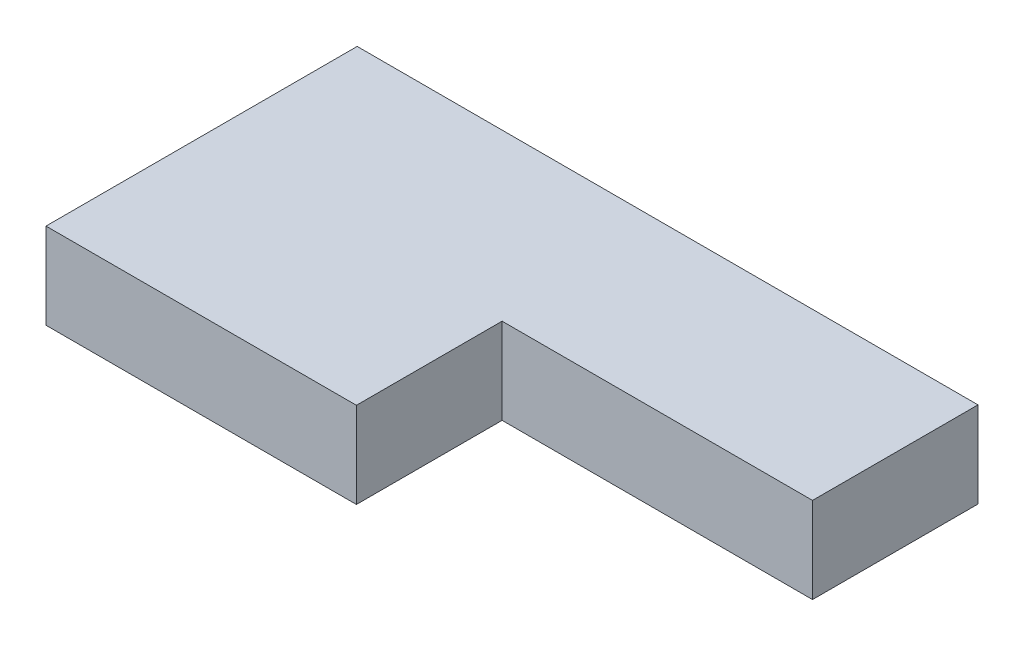
SolidWorks part; units mm, degrees
ref_plane "Front Plane" through (0, 0, 0) normal (0, 0, 1) x (1, 0, 0)
ref_plane "Top Plane" through (0, 0, 0) normal (0, 1, 0) x (1, 0, 0)
ref_plane "Right Plane" through (0, 0, 0) normal (1, 0, 0) x (0, 0, -1)
sketch "Sketch1" plane through (0, 0, 0) normal (0, 1, 0) x (1, 0, 0)
  line L0 (0, 40.6807) -> (91.7709, 40.6807)
  line L1 (91.7709, 40.6807) -> (91.7709, 16.2191)
  line L2 (91.7709, 16.2191) -> (45.8855, 16.2191)
  line L3 (45.8855, 16.2191) -> (45.8855, -5.3177)
  line L4 (45.8855, -5.3177) -> (0, -5.3177)
  line L5 (0, -5.3177) -> (0, 40.6807)
extrude "Extrude1" add sketch "Sketch1" against normal blind 12.7
